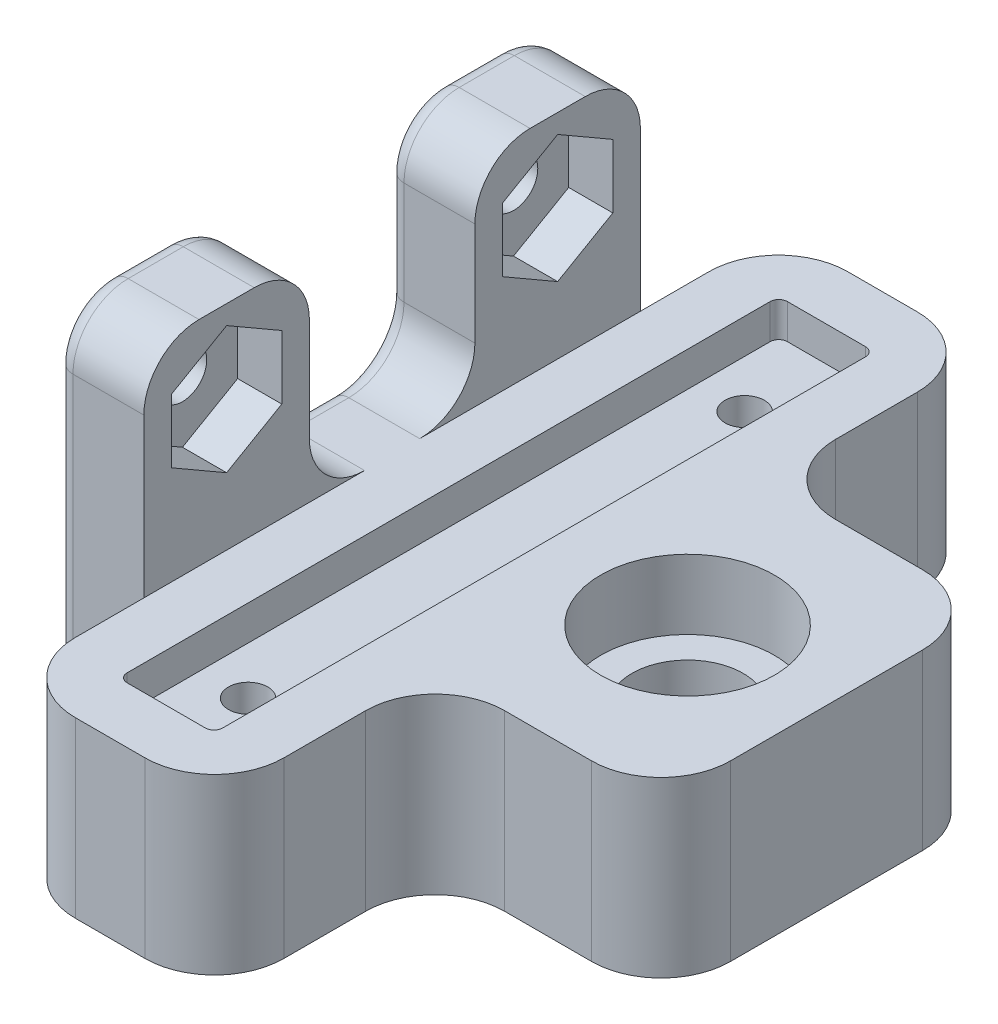
SolidWorks part; units mm, degrees
ref_plane "Front Plane" through (0, 0, 0) normal (0, 0, 1) x (1, 0, 0)
ref_plane "Top Plane" through (0, 0, 0) normal (0, 1, 0) x (1, 0, 0)
ref_plane "Right Plane" through (0, 0, 0) normal (1, 0, 0) x (0, 0, -1)
sketch "Sketch1" plane through (0, 0, 0) normal (0, 1, 0) x (1, 0, 0)
  line L0 (-17, 22.225) -> (-5, 22.225)
  line L1 (-17, -22.225) -> (8, -22.225) construction
  line L2 (-17, -22.225) -> (-17, 22.225)
  line L3 (-17, 22.225) -> (8, 22.225) construction
  line L4 (8, -22.225) -> (8, 22.225) construction
  line L5 (-11, 14.2875) -> (-11, -14.2875) construction
  line L6 (-17, -22.225) -> (-5, -22.225)
  line L7 (-17, 0) -> (8, 0) construction
  line L8 (-5, 22.225) -> (-5, -22.225) construction
  line L10 (-5, 22.225) -> (-5, 9.525)
  line L12 (-5, -22.225) -> (-5, -9.525)
  line L14 (8, 9.525) -> (8, -9.525)
  line L16 (8, 9.525) -> (-5, 9.525)
  line L17 (8, -9.525) -> (-5, -9.525)
  circle A0 centre (0, 0) radius 3.2
  circle A4 centre (-11, 14.2875) radius 1.1303
  circle A7 centre (-11, -14.2875) radius 1.1303
  point P0 (0, 0)
  dimension "D4" = 6.4
  dimension "D6" = 12
  dimension "D8" = 2.2606
  dimension "D1" = 44.45
  dimension "D2" = 25
  dimension "D3" = 8
  dimension "D5" = 6
  dimension "D7" = 14.2875
  dimension "D9" = 19.05
extrude "Boss-Extrude1" add sketch "Sketch1" along normal blind 10
sketch "Sketch2" plane through (0, 10, 0) normal (0, 1, 0) x (1, 0, 0)
  line L0 (-13.75, 0) -> (-8.25, 0) construction
  line L1 (-11, 14.2875) -> (-11, -14.2875) construction
  line L2 (-13.75, -19) -> (-8.25, -19)
  line L3 (-17, 0) -> (8, 0) construction
  line L10 (-8.25, 19) -> (-13.75, 19)
  line L15 (-8.25, -19) -> (-8.25, 19)
  line L16 (-13.75, -19) -> (-13.75, 19)
  point P2 (-11, 0)
  dimension "D1" = 5.5
  dimension "D2" = 38
extrude "Cut-Extrude1" cut sketch "Sketch2" against normal blind 2 contours L16 L10 L15 L2
fillet "Fillet3" radius 0.5 4 edges at (-13.75, 9, 19) (-8.25, 9, 19) (-8.25, 9, -19) (-13.75, 9, -19)
sketch "Sketch5" plane through (0, 10, 0) normal (0, 1, 0) x (1, 0, 0)
  circle A0 centre (0, 0) radius 5
  dimension "D1" = 10
extrude "Cut-Extrude2" cut sketch "Sketch5" against normal blind 4
fillet "Fillet1" radius 4 8 edges at (-17, 5, 22.225) (-5, 5, 22.225) (-5, 5, -9.525) (-5, 5, 9.525) (8, 5, 9.525) (8, 5, -9.525) (-5, 5, -22.225) (-17, 5, -22.225)
sketch "Sketch4" plane through (-17, 0, 0) normal (-1, 0, 0) x (0, 0, 1)
  line L0 (0, 0) -> (0, 35.0651) construction
  line L1 (-18.225, 0) -> (18.225, 0) construction
  line L2 (-4.7625, 10) -> (4.7625, 10)
  line L3 (-4.7625, 10) -> (-4.7625, 22.2875)
  line L5 (4.7625, 10) -> (4.7625, 22.2875)
  line L6 (9.525, 22.2875) -> (9.525, 0) construction
  line L8 (-9.525, 17.525) -> (9.525, 17.525) construction
  line L10 (-4.7625, 22.2875) -> (-14.2875, 22.2875)
  line L11 (-14.2875, 22.2875) -> (-14.2875, 0)
  line L12 (-18.225, 0) -> (18.225, 0) construction
  line L13 (-14.2875, 0) -> (14.2875, 0)
  line L14 (14.2875, 0) -> (14.2875, 22.2875)
  line L15 (14.2875, 22.2875) -> (4.7625, 22.2875)
  line L16 (-18.5, 8) -> (18.5, 8) construction
  line L17 (-18.225, 10) -> (18.225, 10) construction
  circle A0 centre (-9.525, 17.525) radius 1.397
  circle A1 centre (9.525, 17.525) radius 1.397
  point P3 (0, 16.3906)
  point P10 (0, 17.525)
  point P21 (0, 0)
  point P22 (0, 10)
  point P29 (0, 0)
  dimension "D7" = 2.794
  dimension "D1" = 9.525
  dimension "D2" = 4.7625
  dimension "D4" = 19.05
  dimension "D5" = 9.525
extrude "Boss-Extrude2" add sketch "Sketch4" along normal blind 5.08
sketch "Sketch6" plane through (-17, 0, 0) normal (1, 0, 0) x (0, 0, -1)
  line L1 (-6.35, 15.6919) -> (-6.35, 19.3581)
  line L2 (-6.35, 19.3581) -> (-9.525, 21.1912)
  line L3 (-9.525, 21.1912) -> (-12.7, 19.3581)
  line L4 (-12.7, 19.3581) -> (-12.7, 15.6919)
  line L5 (-12.7, 15.6919) -> (-9.525, 13.8588)
  line L6 (-9.525, 13.8588) -> (-6.35, 15.6919)
  circle A0 centre (-9.525, 17.525) radius 3.175 construction
  dimension "D1" = 6.35
extrude "Cut-Extrude3" cut sketch "Sketch6" against normal blind 2.54
ref_plane "Plane1" through (0, 0, 0) normal (0, 0, 1) x (1, 0, 0)
mirror "Mirror1" about plane through (0, 0, 0) normal (0, 0, 1) of "Cut-Extrude3"
fillet "Fillet5" radius 3.175 6 edges at (-19.54, 10, 4.7625) (-19.54, 10, -4.7625) (-19.54, 22.2875, 14.2875) (-19.54, 22.2875, 4.7625) (-19.54, 22.2875, -4.7625) (-19.54, 22.2875, -14.2875)
fillet "Fillet4" radius 1 13 edges at (-22.08, 9.5563, 14.2875) (-22.08, 9.5562, -14.2875) (-22.08, 21.3576, 13.3576) (-22.08, 22.2875, 9.525) (-22.08, 21.3576, 5.6924) (-22.08, 16.1437, 4.7625) (-22.08, 10.9299, 3.8326) (-22.08, 10, 0) (-22.08, 10.9299, -3.8326) (-22.08, 16.1437, -4.7625) (-22.08, 21.3576, -5.6924) (-22.08, 22.2875, -9.525) (-22.08, 21.3576, -13.3576)
